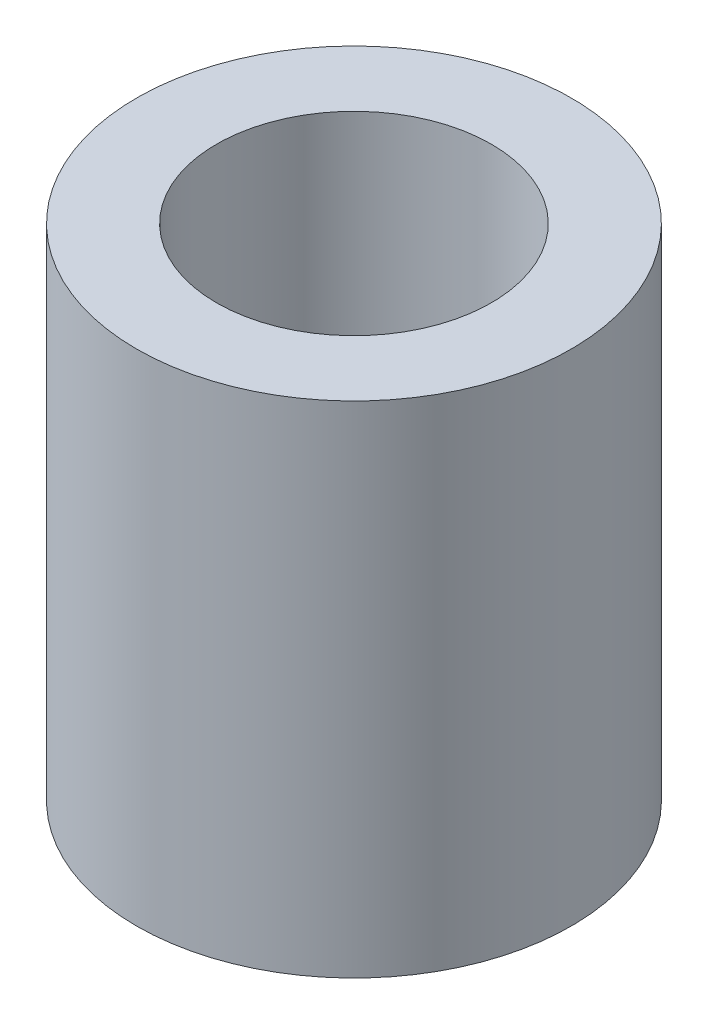
SolidWorks part; units mm, degrees
ref_plane "Front Plane" through (0, 0, 0) normal (0, 0, 1) x (1, 0, 0)
ref_plane "Top Plane" through (0, 0, 0) normal (0, 1, 0) x (1, 0, 0)
ref_plane "Right Plane" through (0, 0, 0) normal (1, 0, 0) x (0, 0, -1)
sketch "Sketch1" plane through (0, 0, 0) normal (0, 1, 0) x (1, 0, 0)
  circle A0 centre (0, 0) radius 4.35
  dimension "D1" = 8.7
extrude "Boss-Extrude1" add sketch "Sketch1" along normal blind 10
sketch "Sketch2" plane through (0, 10, 0) normal (0, 1, 0) x (1, 0, 0)
  circle A0 centre (0, 0) radius 2.75
  circle A1 centre (0, 0) radius 4.35 construction
  dimension "D1" = 1.6
extrude "Cut-Extrude1" cut sketch "Sketch2" against normal blind 9.4
sketch "Sketch3" plane through (0, 0.6, 0) normal (0, 1, 0) x (1, 0, 0)
  circle A0 centre (0, 0) radius 0.475
  dimension "D1" = 0.95
extrude "Cut-Extrude2" cut sketch "Sketch3" against normal through all
